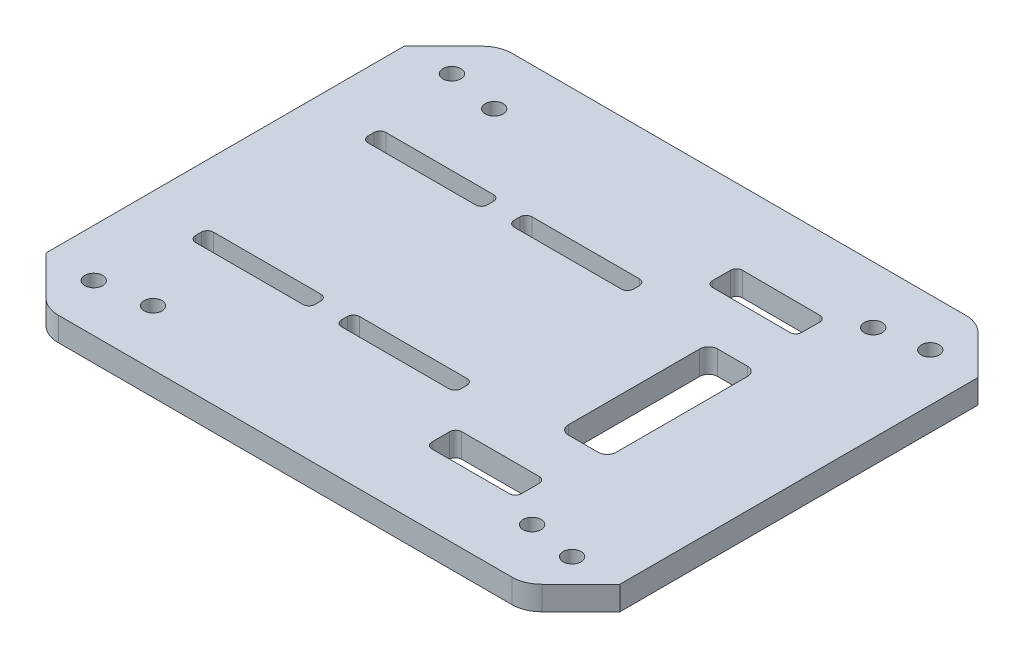
SolidWorks part; units mm, degrees
ref_plane "Front Plane" through (0, 0, 0) normal (0, 0, 1) x (1, 0, 0)
ref_plane "Top Plane" through (0, 0, 0) normal (0, 1, 0) x (1, 0, 0)
ref_plane "Right Plane" through (0, 0, 0) normal (1, 0, 0) x (0, 0, -1)
sketch "Sketch1" plane through (0, 0, 0) normal (0, 1, 0) x (1, 0, 0)
  line L8 (26.7708, 21.7687) -> (26.7832, 24.7686)
  line L9 (12.7668, 20.8263) -> (25.7667, 20.7728)
  line L10 (25.7873, 25.7727) -> (12.7874, 25.8263)
  line L11 (11.7833, 24.8304) -> (11.7709, 21.8304)
  line L12 (28.6131, -11.1668) -> (28.6131, 10.8332)
  line L13 (22.1131, -12.6668) -> (27.1131, -12.6668)
  line L14 (27.1131, 12.3332) -> (22.1131, 12.3332)
  line L15 (20.6131, 10.8332) -> (20.6131, -11.1668)
  line L16 (26.6805, -25.1109) -> (26.6805, -22.1109)
  line L17 (12.6805, -26.1109) -> (25.6805, -26.1109)
  line L18 (11.6805, -22.1109) -> (11.6805, -25.1109)
  line L19 (25.6805, -21.1109) -> (12.6805, -21.1109)
  line L20 (-48.0711, 30) -> (-48.0711, -30)
  line L21 (-37.0711, 15.9529) -> (-19.0711, 15.9529)
  line L22 (-37.0711, 12.9529) -> (-19.0711, 12.9529)
  line L23 (6.3945, 14.9529) -> (6.3945, 13.9529)
  line L24 (-38.0711, 14.9529) -> (-38.0711, 13.9529)
  line L25 (-49.5689, 15.9529) -> (1.9289, 15.9529) construction
  line L26 (-49.5689, 12.9529) -> (1.9289, 12.9529) construction
  line L31 (48.0711, 30) -> (48.0711, -30)
  line L32 (48.0711, 30) -> (41.5355, 36.5355)
  line L33 (38, 38) -> (-38, 38)
  line L34 (-41.5355, 36.5355) -> (-48.0711, 30)
  line L35 (-48.0711, -30) -> (-41.5355, -36.5355)
  line L36 (-38, -38) -> (38, -38)
  line L37 (41.5355, -36.5355) -> (48.0711, -30)
  line L38 (-18.0711, 14.9529) -> (-18.0711, 13.9529)
  line L39 (5.3945, 15.9529) -> (-12.6055, 15.9529)
  line L40 (-13.6055, 14.9529) -> (-13.6055, 13.9529)
  line L41 (-12.6055, 12.9529) -> (5.3945, 12.9529)
  line L43 (-38.0711, -14.9529) -> (-38.0711, -13.9529)
  line L44 (-37.0711, -12.9529) -> (-19.0711, -12.9529)
  line L45 (-18.0711, -14.9529) -> (-18.0711, -13.9529)
  line L46 (-37.0711, -15.9529) -> (-19.0711, -15.9529)
  line L47 (-13.6055, -14.9529) -> (-13.6055, -13.9529)
  line L48 (5.3945, -15.9529) -> (-12.6055, -15.9529)
  line L49 (6.3945, -14.9529) -> (6.3945, -13.9529)
  line L50 (-12.6055, -12.9529) -> (5.3945, -12.9529)
  circle A5 centre (32.0596, -28.6916) radius 1.5
  circle A7 centre (32.0596, 28.4584) radius 1.5
  arc A8 (26.7832, 24.7686) -> (25.7873, 25.7727) centre (25.7832, 24.7728) ccw
  arc A9 (25.7667, 20.7728) -> (26.7708, 21.7687) centre (25.7708, 21.7728) ccw
  arc A10 (12.7874, 25.8263) -> (11.7833, 24.8304) centre (12.7833, 24.8263) ccw
  arc A11 (11.7709, 21.8304) -> (12.7668, 20.8263) centre (12.7709, 21.8263) ccw
  arc A12 (20.6131, -11.1668) -> (22.1131, -12.6668) centre (22.1131, -11.1668) ccw
  arc A13 (27.1131, -12.6668) -> (28.6131, -11.1668) centre (27.1131, -11.1668) ccw
  arc A14 (28.6131, 10.8332) -> (27.1131, 12.3332) centre (27.1131, 10.8332) ccw
  arc A15 (22.1131, 12.3332) -> (20.6131, 10.8332) centre (22.1131, 10.8332) ccw
  arc A16 (26.6805, -22.1109) -> (25.6805, -21.1109) centre (25.6805, -22.1109) ccw
  arc A17 (25.6805, -26.1109) -> (26.6805, -25.1109) centre (25.6805, -25.1109) ccw
  arc A18 (11.6805, -25.1109) -> (12.6805, -26.1109) centre (12.6805, -25.1109) ccw
  arc A19 (12.6805, -21.1109) -> (11.6805, -22.1109) centre (12.6805, -22.1109) ccw
  circle A21 centre (-31.4404, -28.6916) radius 1.5
  circle A23 centre (-31.4404, 28.4584) radius 1.5
  arc A24 (6.3945, 13.9529) -> (5.3945, 12.9529) centre (5.3945, 13.9529) cw
  arc A25 (5.3945, 15.9529) -> (6.3945, 14.9529) centre (5.3945, 14.9529) cw
  arc A26 (-38.0711, 13.9529) -> (-37.0711, 12.9529) centre (-37.0711, 13.9529) ccw
  arc A27 (-38.0711, 14.9529) -> (-37.0711, 15.9529) centre (-37.0711, 14.9529) cw
  arc A32 (41.5355, 36.5355) -> (38, 38) centre (38, 33) ccw
  arc A33 (-38, 38) -> (-41.5355, 36.5355) centre (-38, 33) ccw
  arc A34 (-41.5355, -36.5355) -> (-38, -38) centre (-38, -33) ccw
  arc A35 (38, -38) -> (41.5355, -36.5355) centre (38, -33) ccw
  arc A36 (-19.0711, 12.9529) -> (-18.0711, 13.9529) centre (-19.0711, 13.9529) ccw
  arc A37 (-19.0711, 15.9529) -> (-18.0711, 14.9529) centre (-19.0711, 14.9529) cw
  arc A38 (-13.6055, 13.9529) -> (-12.6055, 12.9529) centre (-12.6055, 13.9529) ccw
  arc A39 (-13.6055, 14.9529) -> (-12.6055, 15.9529) centre (-12.6055, 14.9529) cw
  arc A40 (-38.0711, -14.9529) -> (-37.0711, -15.9529) centre (-37.0711, -14.9529) ccw
  arc A41 (-38.0711, -13.9529) -> (-37.0711, -12.9529) centre (-37.0711, -13.9529) cw
  arc A42 (-19.0711, -12.9529) -> (-18.0711, -13.9529) centre (-19.0711, -13.9529) cw
  arc A43 (-19.0711, -15.9529) -> (-18.0711, -14.9529) centre (-19.0711, -14.9529) ccw
  arc A44 (-13.6055, -14.9529) -> (-12.6055, -15.9529) centre (-12.6055, -14.9529) ccw
  arc A45 (5.3945, -15.9529) -> (6.3945, -14.9529) centre (5.3945, -14.9529) ccw
  arc A46 (6.3945, -13.9529) -> (5.3945, -12.9529) centre (5.3945, -13.9529) ccw
  arc A47 (-13.6055, -13.9529) -> (-12.6055, -12.9529) centre (-12.6055, -13.9529) cw
  point P3 (0, 0)
  point P114 (0, 0)
  dimension "D4" = 20
  dimension "D5" = 1
  dimension "D6" = 10
  dimension "D7" = 15
  dimension "D11" = 1
  dimension "D13" = 20
  dimension "D12" = 1
  dimension "D2" = 96.1421
  dimension "D3" = 76
  dimension "D8" = 5
  dimension "D9" = 8
  dimension "D10" = 25
extrude "Boss-Extrude1" add sketch "Sketch1" along normal blind 4
sketch "Sketch2" plane through (0, 4, 0) normal (0, 1, 0) x (1, 0, 0)
  line L1 (-48.0711, 30) -> (-48.0711, -30) construction
  circle A0 centre (-40.0711, 30) radius 1.5
  circle A1 centre (40.0711, 30) radius 1.5
  circle A2 centre (40.0711, -30) radius 1.5
  circle A3 centre (-40.0711, -30) radius 1.5
  dimension "D1" = 3
  dimension "D2" = 8
extrude "Cut-Extrude1" cut sketch "Sketch2" against normal blind 10
